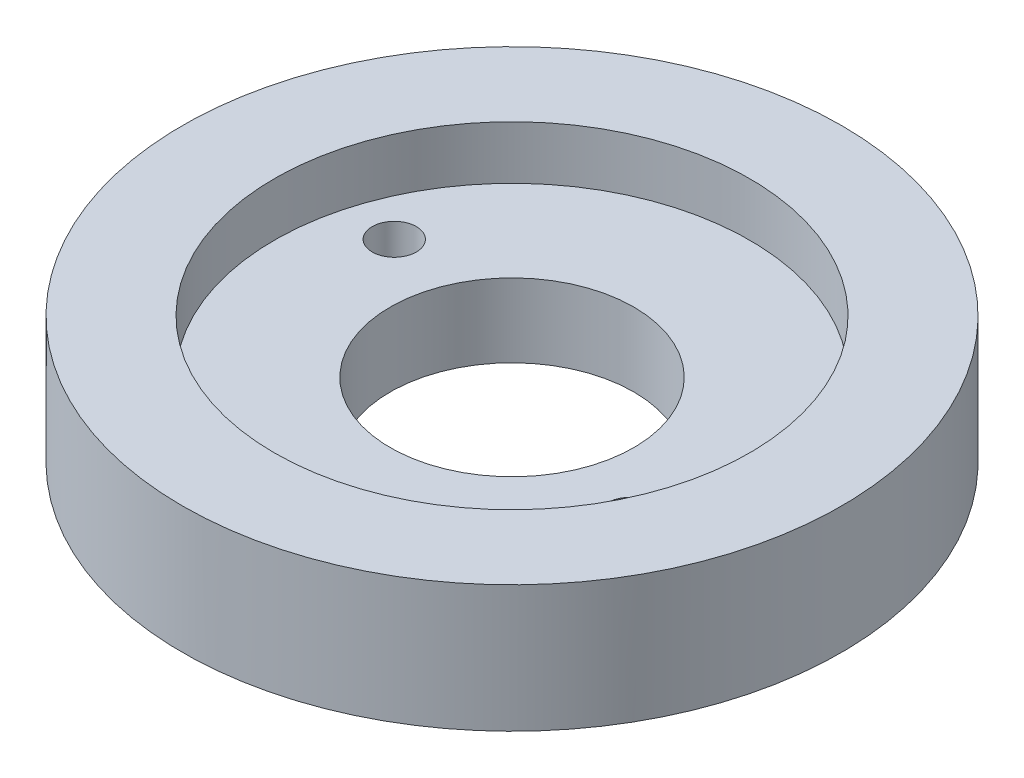
SolidWorks part; units mm, degrees
ref_plane "Front Plane" through (0, 0, 0) normal (0, 0, 1) x (1, 0, 0)
ref_plane "Top Plane" through (0, 0, 0) normal (0, 1, 0) x (1, 0, 0)
ref_plane "Right Plane" through (0, 0, 0) normal (1, 0, 0) x (0, 0, -1)
sketch "Sketch2" plane through (0, 0, 0) normal (0, 1, 0) x (1, 0, 0)
  circle A0 centre (0, 0) radius 35.85
  dimension "D1" = 71.7
extrude "Boss-Extrude3" add sketch "Sketch2" along normal blind 11.8024
sketch "Sketch3" plane through (0, 0, 0) normal (0, -1, 0) x (1, 0, 0)
  circle A0 centre (0, 0) radius 13.25
  dimension "D1" = 26.5
extrude "Cut-Extrude1" cut sketch "Sketch3" against normal blind 6
shell "Shell1" thickness 10
sketch "Sketch4" plane through (0, 16, 0) normal (0, 1, 0) x (1, 0, 0)
  circle A0 centre (0, 0) radius 23.25
extrude "Cut-Extrude2" cut sketch "Sketch4" against normal blind 6
sketch "Sketch5" plane through (0, 10, 0) normal (0, 1, 0) x (1, 0, 0)
  circle A1 centre (0, 0) radius 25.85
extrude "Cut-Extrude3" cut sketch "Sketch5" against normal blind 4
sketch "Sketch6" plane through (0, 0, 0) normal (0, -1, 0) x (1, 0, 0)
  line L0 (-33.941, -11.5424) -> (33.941, 11.5424)
  line L1 (0, 0) -> (19.4084, 6.6003) construction
  circle A0 centre (0, 0) radius 35.85 construction
  circle A1 centre (-19.4084, -6.6003) radius 2.4
  circle A2 centre (19.4084, 6.6003) radius 2.4
  point P6 (0, 0)
  dimension "D1" = 4.8
  dimension "D3" = 4.8
  dimension "D2" = 20.5
  dimension "D4" = 20.5
extrude "Cut-Extrude4" cut sketch "Sketch6" against normal blind 18 contours A2 | A1
sketch "Sketch7" plane through (0, 0, 0) normal (0, -1, 0) x (1, 0, 0)
  circle A0 centre (0, 0) radius 35.85
extrude "Boss-Extrude4" add sketch "Sketch7" along normal blind 2
sketch "Sketch8" plane through (0, -2, 0) normal (0, -1, 0) x (1, 0, 0)
  circle A0 centre (-19.4084, -6.6003) radius 2.4 construction
  circle A1 centre (19.4084, 6.6003) radius 2.4 construction
  circle A8 centre (19.4084, 6.6003) radius 2.4
  circle A9 centre (-19.4084, -6.6003) radius 2.4
  circle A10 centre (-19.4084, -6.6003) radius 5
  circle A11 centre (19.4084, 6.6003) radius 5
  circle A13 centre (0, 0) radius 13.25
  circle A14 centre (0, 0) radius 13.25
  circle A15 centre (0, 0) radius 13.25
  dimension "D1" = 0
extrude "Cut-Extrude6" cut sketch "Sketch8" against normal blind 2 contours A10 | A13 | A11
